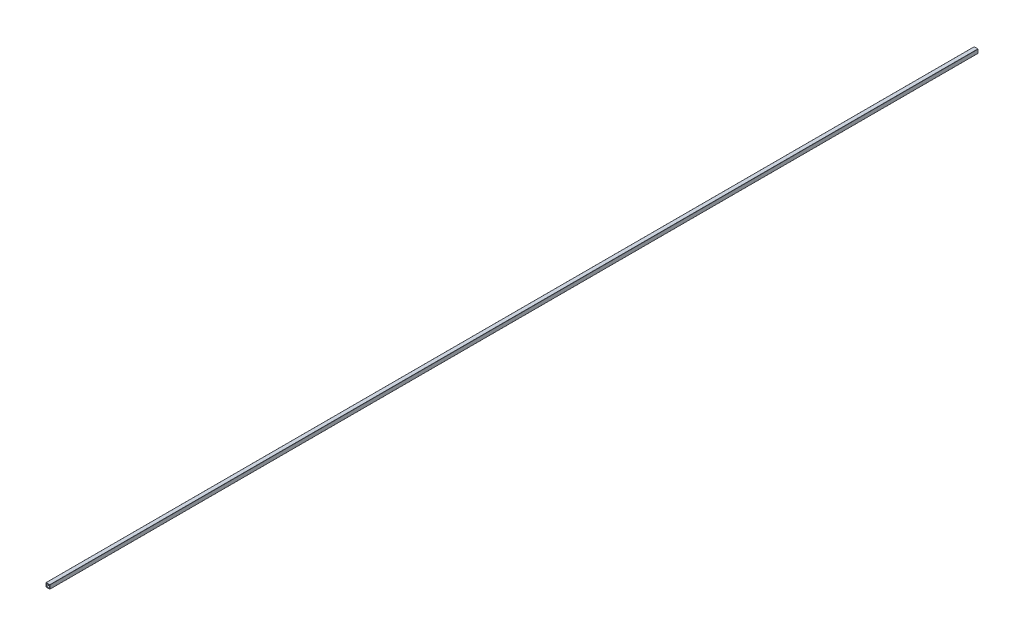
SolidWorks part; units mm, degrees
material "AISI 1035 Acero (SS)"
ref_plane "Alzado" through (0, 0, 0) normal (0, 0, 1) x (1, 0, 0)
ref_plane "Planta" through (0, 0, 0) normal (0, 1, 0) x (1, 0, 0)
ref_plane "Vista lateral" through (0, 0, 0) normal (1, 0, 0) x (0, 0, -1)
sketch "Croquis1" plane through (0, 0, 0) normal (0, 0, 1) x (1, 0, 0)
  line L0 (-9.28, -9.28) -> (-9.28, 9.28)
  line L1 (-11.7, -12.7) -> (11.7, -12.7)
  line L2 (-12.7, -11.7) -> (-12.7, 11.7)
  line L3 (-11.7, 12.7) -> (11.7, 12.7)
  line L4 (12.7, -11.7) -> (12.7, 11.7)
  line L5 (-12.7, -12.7) -> (12.7, 12.7) construction
  line L6 (-12.7, 12.7) -> (12.7, -12.7) construction
  line L7 (-9.28, 9.28) -> (9.28, 9.28)
  line L8 (9.28, -9.28) -> (9.28, 9.28)
  line L9 (-9.28, -9.28) -> (9.28, -9.28)
  line L10 (-12.7, -12.7) -> (12.7, -12.7) construction
  line L11 (12.7, -12.7) -> (12.7, 12.7) construction
  line L12 (-12.7, 12.7) -> (12.7, 12.7) construction
  line L13 (-12.7, -12.7) -> (-12.7, 12.7) construction
  arc A0 (11.7, -12.7) -> (12.7, -11.7) centre (11.7, -11.7) ccw
  arc A1 (11.7, 12.7) -> (12.7, 11.7) centre (11.7, 11.7) cw
  arc A2 (-11.7, -12.7) -> (-12.7, -11.7) centre (-11.7, -11.7) cw
  arc A3 (-12.7, 11.7) -> (-11.7, 12.7) centre (-11.7, 11.7) cw
  point P0 (0, 0)
  dimension "D4" = 1
  dimension "D1" = 25.4
  dimension "D2" = 25.4
  dimension "D3" = 3.42
extrude "Saliente-Extruir1" add sketch "Croquis1" along normal blind 6000
